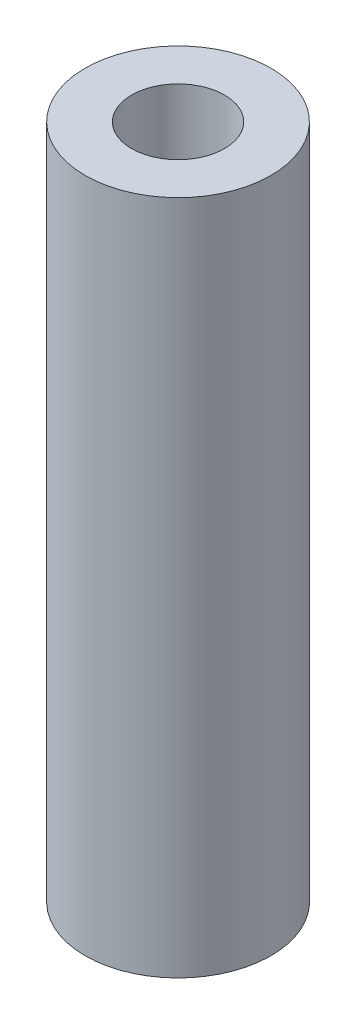
SolidWorks part; units mm, degrees
ref_plane "Front Plane" through (0, 0, 0) normal (0, 0, 1) x (1, 0, 0)
ref_plane "Top Plane" through (0, 0, 0) normal (0, 1, 0) x (1, 0, 0)
ref_plane "Right Plane" through (0, 0, 0) normal (1, 0, 0) x (0, 0, -1)
sketch "Sketch1" plane through (0, 0, 0) normal (0, 1, 0) x (1, 0, 0)
  line L0 (0, 0) -> (0, 12412.8191) construction
  line L1 (0, 0) -> (12412.8191, 0) construction
  circle A0 centre (0, 0) radius 11
  circle A1 centre (0, 0) radius 5.5
  dimension "D1" = 22
  dimension "D2" = 11
extrude "Boss-Extrude1" add sketch "Sketch1" along normal mid plane 80
